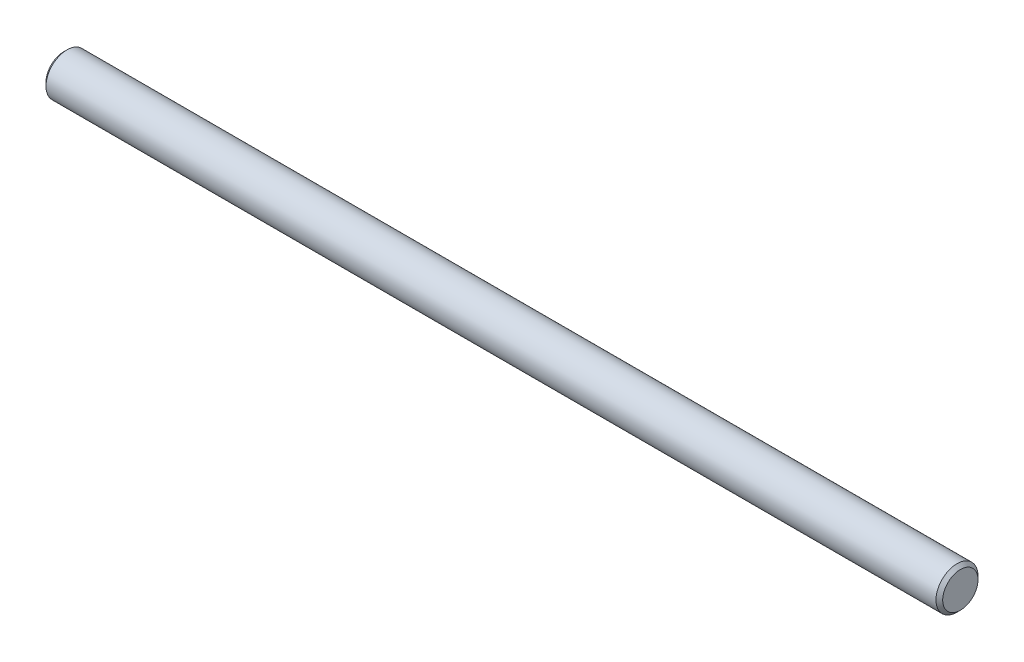
SolidWorks part; units mm, degrees
material "AISI 304"
ref_plane "Front" through (0, 0, 0) normal (0, 0, 1) x (1, 0, 0)
ref_plane "Top" through (0, 0, 0) normal (0, 1, 0) x (1, 0, 0)
ref_plane "Right" through (0, 0, 0) normal (1, 0, 0) x (0, 0, -1)
sketch "Sketch1" plane through (0, 0, 0) normal (1, 0, 0) x (0, 0, -1)
  circle A0 centre (0, 0) radius 2.3812
  dimension "D1" = 4.7625
extrude "Extrude1" add sketch "Sketch1" along normal mid plane 101.6
chamfer "Chamfer1" distance 0.381 angle 45 2 edges at (-50.8, 0, -2.3812) (50.8, 0, -2.3812)
